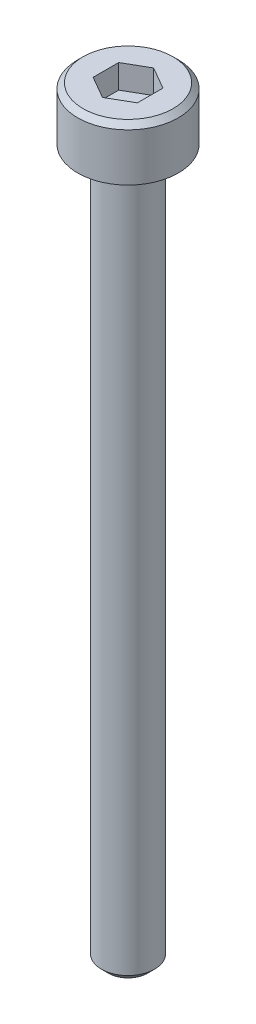
SolidWorks part; units mm, degrees
ref_plane "Front Plane" through (0, 0, 0) normal (0, 0, 1) x (1, 0, 0)
ref_plane "Top Plane" through (0, 0, 0) normal (0, 1, 0) x (1, 0, 0)
ref_plane "Right Plane" through (0, 0, 0) normal (1, 0, 0) x (0, 0, -1)
sketch "Sketch1" plane through (0, 0, 0) normal (0, 0, 1) x (1, 0, 0)
  line L0 (0, -40) -> (1.1, -40)
  line L1 (1.1, -40) -> (1.5, -39.6)
  line L2 (1.5, -39.6) -> (1.5, 0)
  line L3 (1.5, 0) -> (2.84, 0)
  line L4 (2.84, 0) -> (2.84, 2.7)
  line L5 (2.84, 2.7) -> (2.54, 3)
  line L6 (2.54, 3) -> (0, 3)
  line L7 (0, 3) -> (0, -40)
  line L8 (0, -10) -> (0, 1000) construction
revolve "Revolve1" add sketch "Sketch1" angle 360 about L8
cosmetic thread "Cosmetic Thread1" parameters "D1"=39.6, "D2"=2.4588
ref_plane "Plane1" through (0, 3, 0) normal (0, 1, 0) x (1, 0, 0)
sketch "Sketch2" plane through (0, 3, 0) normal (0, 1, 0) x (1, 0, 0)
  line L0 (1.25, -0.7217) -> (0, -1.4434)
  line L1 (0, -1.4434) -> (-1.25, -0.7217)
  line L2 (-1.25, -0.7217) -> (-1.25, 0.7217)
  line L3 (-1.25, 0.7217) -> (0, 1.4434)
  line L4 (0, 1.4434) -> (1.25, 0.7217)
  line L5 (1.25, 0.7217) -> (1.25, -0.7217)
extrude "Cut-Extrude1" cut sketch "Sketch2" against normal blind 1.35
